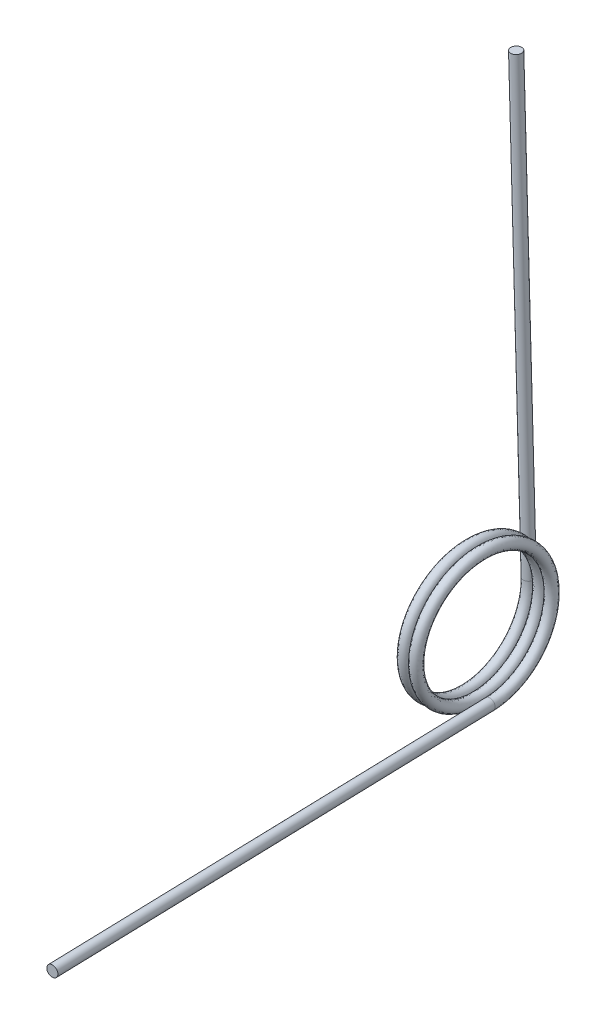
SolidWorks part; units mm, degrees
ref_plane "Front" through (0, 0, 0) normal (0, 0, 1) x (1, 0, 0)
ref_plane "Top" through (0, 0, 0) normal (0, 1, 0) x (1, 0, 0)
ref_plane "Right" through (0, 0, 0) normal (1, 0, 0) x (0, 0, -1)
sketch "Sketch1" plane through (0, 0, 0) normal (1, 0, 0) x (0, 0, -1)
  line L0 (0, 0) -> (0, -2.5146) construction
  line L1 (0, -2.5146) -> (0, -2.7432) construction
  line L2 (0, -2.7432) -> (0, -2.9718) construction
  circle A0 centre (0, 0) radius 2.5146 construction
  circle A1 centre (0, 0) radius 2.9718 construction
  circle A2 centre (0, 0) radius 2.7432
  circle A3 centre (0, -2.7432) radius 0.2286 construction
  circle A4 centre (0, 0) radius 1.9812 construction
  dimension "Wire Dia" = 0.4572
  dimension "Spring OD" = 5.9436
  dimension "Max Rod OD" = 3.9624
curve "Helix/Spiral1" pitch 0.4826 height 1.0858 turns 2.25
ref_plane "Plane1" through (0, 0, -2.7432) normal (0.028, -0.9996, 0) x (0.9996, 0.028, 0)
sketch "Sketch2" plane through (0, 0, -2.7432) normal (0.028, -0.9996, 0) x (0.9996, 0.028, 0)
  circle A0 centre (0, 0) radius 0.2286
  dimension "D1" = 0.4572
sweep "Sweep1" add profiles "Sketch2" path "Helix/Spiral1"
sketch "Sketch3" plane through (0, 0, 0) normal (-0.028, 0.9996, 0) x (-0.9996, -0.028, 0)
  circle A1 centre (0, -2.7432) radius 0.2286
  circle A2 centre (0, -2.7432) radius 0.2286
  dimension "D1" = 0
extrude "Extrude1" add sketch "Sketch3" along normal blind 19.05
sketch "Sketch4" plane through (0.0009, 0, 0.0304) normal (0.028, 0, 0.9996) x (0.9996, 0, -0.028)
  circle A1 centre (1.0854, -2.7432) radius 0.2286
  circle A2 centre (1.0854, -2.7432) radius 0.2286
  dimension "D1" = 0
extrude "Extrude2" add sketch "Sketch4" along normal blind 19.05
sketch "Sketch5" plane through (0, 0, 0) normal (1, 0, 0) x (0, 0, -1)
  circle A0 centre (0, 0) radius 1.9812 construction
  circle A1 centre (0, 0) radius 1.9812
equation "\"D4@Helix/Spiral1\"=\"Wire Dia@Sketch1\"+.001"
equation "\"D1@Sketch2\"=\"Wire Dia@Sketch1\""
equation "\"D1@Extrude2\"=\"Leg Length@Extrude1\""
